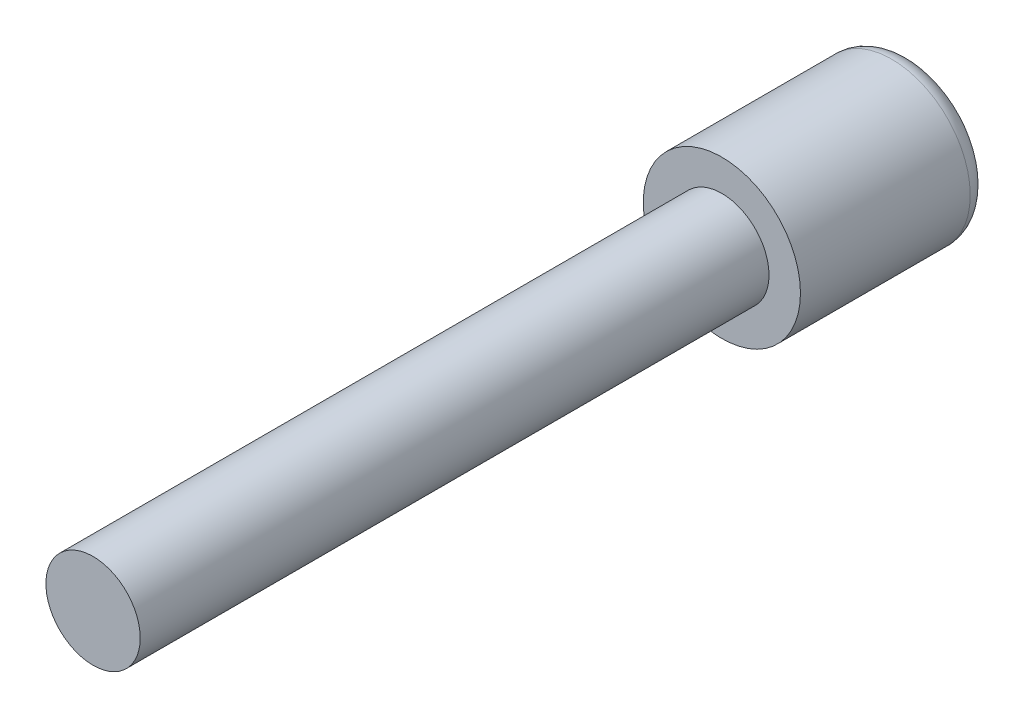
SolidWorks part; units mm, degrees
ref_plane "Front Plane" through (0, 0, 0) normal (0, 0, 1) x (1, 0, 0)
ref_plane "Top Plane" through (0, 0, 0) normal (0, 1, 0) x (1, 0, 0)
ref_plane "Right Plane" through (0, 0, 0) normal (1, 0, 0) x (0, 0, -1)
sketch "Sketch1" plane through (0, 0, 0) normal (0, 0, 1) x (1, 0, 0)
  circle A0 centre (0, 0) radius 1.25
  dimension "D1" = 2.5
extrude "Boss-Extrude1" add sketch "Sketch1" along normal blind 3
sketch "Sketch2" plane through (0, 0, 3) normal (0, 0, 1) x (1, 0, 0)
  circle A0 centre (0, 0) radius 0.75
  dimension "D1" = 1.5
extrude "Boss-Extrude2" add sketch "Sketch2" along normal blind 10
fillet "Fillet2" radius 0.3 1 edges at (1.25, 0, 0)
